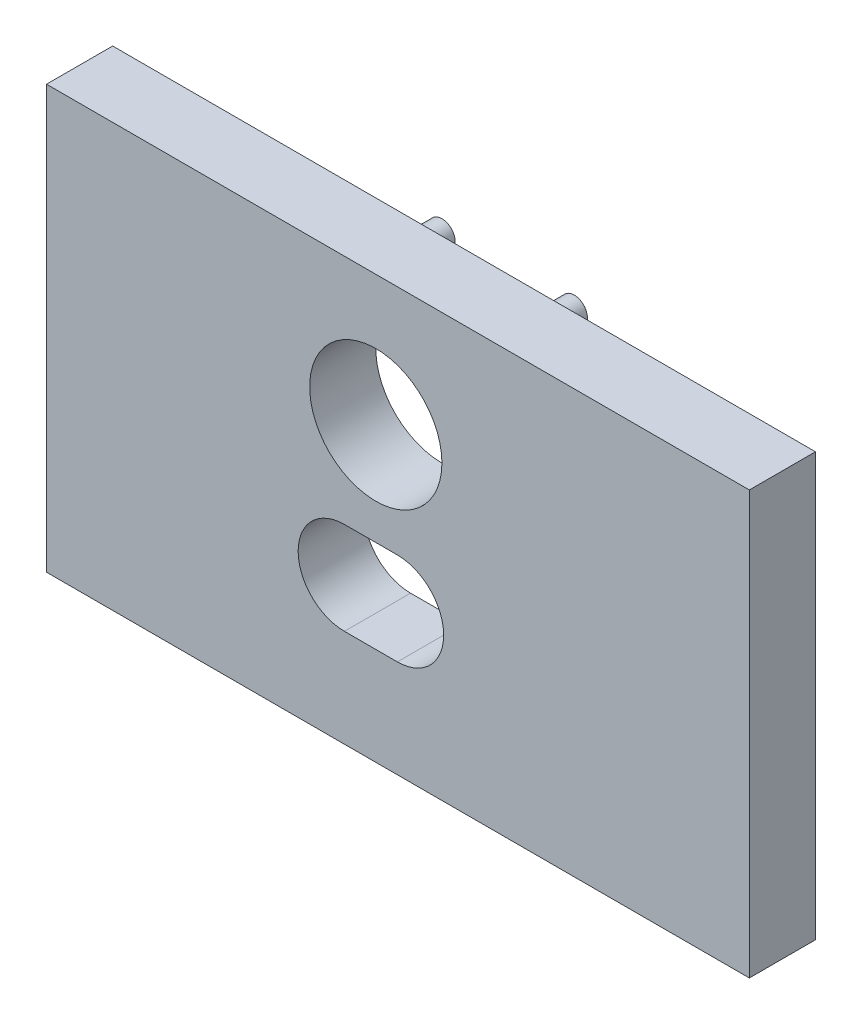
SolidWorks part; units mm, degrees
ref_plane "前视基准面" through (0, 0, 0) normal (0, 0, 1) x (1, 0, 0)
ref_plane "上视基准面" through (0, 0, 0) normal (0, 1, 0) x (1, 0, 0)
ref_plane "右视基准面" through (0, 0, 0) normal (1, 0, 0) x (0, 0, -1)
other "Configuration Table"
sketch "草图1" plane through (0, 0, 0) normal (0, 0, 1) x (1, 0, 0)
  line L1 (-40.8719, 31.4899) -> (12.2616, 31.4899)
  line L2 (-40.8719, 31.4899) -> (-40.8719, -0.4645)
  line L3 (-40.8719, -0.4645) -> (12.2616, -0.4645)
  line L4 (12.2616, 31.4899) -> (12.2616, -0.4645)
extrude "凸台-拉伸1" add sketch "草图1" along normal blind 5
sketch "草图2" plane through (0, 0, 0) normal (0, 0, -1) x (-1, 0, 0)
  line L0 (-12.2616, -0.4645) -> (-12.2616, 31.4899) construction
  line L1 (-10.2616, 29.4899) -> (38.8719, 29.4899)
  line L2 (-10.2616, 29.4899) -> (-10.2616, 1.5355)
  line L3 (-10.2616, 1.5355) -> (38.8719, 1.5355)
  line L4 (38.8719, 29.4899) -> (38.8719, 1.5355)
  line L5 (-12.2616, 31.4899) -> (40.8719, 31.4899) construction
  line L6 (40.8719, 31.4899) -> (40.8719, -0.4645) construction
  line L7 (40.8719, -0.4645) -> (-12.2616, -0.4645) construction
  line L9 (-12.2616, 31.4899) -> (40.8719, 31.4899)
  line L10 (-12.2616, 31.4899) -> (-12.2616, -0.4645)
  line L11 (-12.2616, -0.4645) -> (40.8719, -0.4645)
  line L12 (40.8719, 31.4899) -> (40.8719, -0.4645)
  dimension "D1" = 2
  dimension "D2" = 2
  dimension "D3" = 2
  dimension "D4" = 2
extrude "切除-拉伸1" [suppressed] cut sketch "草图2" against normal blind 3
sketch "草图3" plane through (0, 0, 0) normal (0, 0, -1) x (-1, 0, 0)
  line L1 (27.837, -21.8879) -> (-73.163, -21.8879)
  line L2 (27.837, -21.8879) -> (27.837, 29.1121)
  line L3 (27.837, 29.1121) -> (-73.163, 29.1121)
  line L4 (-73.163, -21.8879) -> (-73.163, 29.1121)
  line L5 (27.837, -21.8879) -> (-73.163, 29.1121) construction
  line L6 (27.837, 29.1121) -> (-73.163, -21.8879) construction
  point P0 (-22.663, 3.6121)
  point P5 (-22.663, 3.6121)
  dimension "D1" = 51
  dimension "D2" = 101
extrude "切除-拉伸2" [suppressed] cut sketch "草图3" against normal blind 4.5
sketch "草图4" [suppressed] plane through (0, 0, 0) normal (0, 0, -1) x (-1, 0, 0)
  line L0 (-93.163, -23.8879) -> (-85.163, -23.8879)
  line L1 (-93.163, 39.1121) -> (-85.163, 39.1121)
  line L2 (-93.163, 39.1121) -> (-93.163, 31.1121)
  line L3 (-93.163, 31.1121) -> (-85.163, 31.1121)
  line L4 (-85.163, 39.1121) -> (-85.163, 31.1121)
  line L5 (-93.163, -23.8879) -> (-93.163, -31.8879)
  line L6 (-93.163, -31.8879) -> (-85.163, -31.8879)
  line L7 (-85.163, -23.8879) -> (-85.163, -31.8879)
  line L8 (34.837, 39.1121) -> (42.837, 39.1121)
  line L9 (34.837, 39.1121) -> (34.837, 31.1121)
  line L10 (34.837, 31.1121) -> (42.837, 31.1121)
  line L11 (42.837, 39.1121) -> (42.837, 31.1121)
  line L12 (34.837, -23.8879) -> (42.837, -23.8879)
  line L13 (34.837, -23.8879) -> (34.837, -31.8879)
  line L14 (34.837, -31.8879) -> (42.837, -31.8879)
  line L15 (42.837, -23.8879) -> (42.837, -31.8879)
  dimension "D1" = 8
  dimension "D2" = 8
  dimension "D3" = 8
extrude "凸台-拉伸2" [suppressed] add sketch "草图4" along normal blind 8
sketch "草图5" [suppressed] plane through (0, 0, 4.5) normal (0, 0, -1) x (-1, 0, 0)
  circle A4 centre (-70.0525, 26.7137) radius 1.5
  circle A5 centre (-69.9255, -19.2603) radius 1.5
  circle A6 centre (24.8167, -19.0063) radius 1.5
  circle A7 centre (24.8167, 26.7137) radius 1.5
extrude "凸台-拉伸3" [suppressed] add sketch "草图5" along normal blind 1
sketch "草图6" [suppressed] plane through (0, 0, 3.5) normal (0, 0, -1) x (-1, 0, 0)
  circle A0 centre (-70.0525, 26.7137) radius 1
  circle A1 centre (-69.9255, -19.2603) radius 1
  circle A2 centre (24.8167, -19.0063) radius 1
  circle A3 centre (24.8167, 26.7137) radius 1
extrude "凸台-拉伸4" [suppressed] add sketch "草图6" along normal blind 3
hole_wizard "M3 六角凹锥坑螺钉的锥形沉头孔1" [suppressed] positions "3D草图1" profile "草图8" countersink size "M3" standard "ISO"
sketch3d "3D草图1"
  point P0 (-86.9377, 36.3345, -2.5)
  point P3 (-86.9377, -26.6655, -2.5)
sketch "草图8" plane through (-44.837, 35.1121, -4) normal (0, 1, 0) x (0, 0, 1)
  line L0 (0, 0) -> (0, 12)
  line L1 (0, 12) -> (1.7, 10.9785)
  line L2 (1.7, 10.9785) -> (1.7, 1.66)
  line L3 (1.7, 1.66) -> (3.36, 0)
  line L4 (3.36, 0) -> (0, 0)
  line L5 (-1.7, 1.66) -> (-3.36, 0) construction
  line L6 (0, 12) -> (-1.7, 10.9785) construction
  line L7 (0, -6.35) -> (0, 107.95) construction
  dimension "孔直径" = 3.4
  dimension "孔深度" = 12
  dimension "近端锥形沉头孔直径" = 6.72
  dimension "近端锥形沉头孔角度" = 90
  dimension "导头角度" = 118
hole_wizard "M3 六角凹锥坑螺钉的锥形沉头孔2" [suppressed] positions "3D草图2" profile "草图9" countersink size "M3" standard "ISO"
sketch3d "3D草图2"
  point P0 (53.0623, -26.6655, -2.5)
  point P3 (53.0623, 36.3345, -2.5)
sketch "草图9" plane through (95.163, -27.8879, -4) normal (0, 1, 0) x (0, 0, -1)
  line L0 (0, 0) -> (0, 12)
  line L1 (0, 12) -> (1.7, 10.9785)
  line L2 (1.7, 10.9785) -> (1.7, 1.66)
  line L3 (1.7, 1.66) -> (3.36, 0)
  line L4 (3.36, 0) -> (0, 0)
  line L5 (-1.7, 1.66) -> (-3.36, 0) construction
  line L6 (0, 12) -> (-1.7, 10.9785) construction
  line L7 (0, -6.35) -> (0, 107.95) construction
  dimension "孔直径" = 3.4
  dimension "孔深度" = 12
  dimension "近端锥形沉头孔直径" = 6.72
  dimension "近端锥形沉头孔角度" = 90
  dimension "导头角度" = 118
thread "螺纹线1" [suppressed] pitch 0.5 start angle 0, offset 0, length 8, pitch 0.5, diameter 3.4
ref_plane "基准面1" through (85.163, 35.1121, -5.7) normal (0, -1, 0) x (0, 0, -1)
sketch "螺纹线轮廓1" plane through (85.163, 35.1121, -5.7) normal (0, -1, 0) x (0, 0, -1)
  line L0 (0, 0) -> (0, 0.5) construction
  line L11 (0, 0) -> (0, 0.4375)
  line L12 (0, 0.4375) -> (-0.2706, 0.2812)
  line L13 (-0.2706, 0.2812) -> (-0.2706, 0.1562)
  line L15 (-0.2706, 0.1562) -> (0, 0)
  line L17 (-0.2706, 0.2187) -> (0, 0.2187) construction
  point P2 (0, 0)
  dimension "Pitch" = 0.5
  dimension "Profile_Angle" = 60
  dimension "Profile_Land" = 0.125
  dimension "Profile_Height" = 0.2706
sketch "草图10" [suppressed] plane through (0, -33.8879, 0) normal (0, -1, 0) x (1, 0, 0)
  line L1 (-44.837, 5) -> (95.163, 5)
  line L2 (-44.837, 5) -> (-44.837, 3)
  line L3 (-44.837, 3) -> (95.163, 3)
  line L4 (95.163, 5) -> (95.163, 3)
extrude "凸台-拉伸5" [suppressed] add sketch "草图10" along normal blind 5
sketch "草图11" [suppressed] plane through (0, 0, 0) normal (0, 0, -1) x (-1, 0, 0)
  line L0 (27.837, 29.1121) -> (-73.163, 29.1121) construction
  line L1 (12.837, 29.1121) -> (27.837, 29.1121)
  line L2 (12.837, 29.1121) -> (12.837, 28.1121)
  line L3 (12.837, -21.8879) -> (27.837, -21.8879)
  line L4 (27.837, 29.1121) -> (27.837, -21.8879)
  line L5 (12.837, -20.8879) -> (12.837, -21.8879)
  line L6 (12.837, 28.1121) -> (26.837, 28.1121)
  line L8 (12.837, -20.8879) -> (26.837, -20.8879)
  line L9 (26.837, 28.1121) -> (26.837, -20.8879)
  dimension "D1" = 1
  dimension "D2" = 1
  dimension "D3" = 1
  dimension "D4" = 15
extrude "凸台-拉伸6" [suppressed] add sketch "草图11" against normal blind 1
thread "螺纹线2" [suppressed] pitch 0.5 start angle 0, offset 0, length 8, pitch 0.5, diameter 3.4
ref_plane "基准面2" through (-34.837, 35.1121, -2.3) normal (0, -1, 0) x (0, 0, 1)
sketch "螺纹线轮廓2" plane through (-34.837, 35.1121, -2.3) normal (0, -1, 0) x (0, 0, 1)
  line L0 (0, 0) -> (0, 0.5) construction
  line L11 (0, 0) -> (0, 0.4375)
  line L12 (0, 0.4375) -> (-0.2706, 0.2812)
  line L13 (-0.2706, 0.2812) -> (-0.2706, 0.1562)
  line L15 (-0.2706, 0.1562) -> (0, 0)
  line L17 (-0.2706, 0.2187) -> (0, 0.2187) construction
  point P2 (0, 0)
  dimension "Pitch" = 0.5
  dimension "Profile_Angle" = 60
  dimension "Profile_Land" = 0.125
  dimension "Profile_Height" = 0.2706
thread "螺纹线3" [suppressed] pitch 0.5 start angle 0, offset 0, length 8, pitch 0.5, diameter 3.4
ref_plane "基准面3" through (85.163, -27.8879, -5.7) normal (0, -1, 0) x (0, 0, -1)
sketch "螺纹线轮廓3" plane through (85.163, -27.8879, -5.7) normal (0, -1, 0) x (0, 0, -1)
  line L0 (0, 0) -> (0, 0.5) construction
  line L11 (0, 0) -> (0, 0.4375)
  line L12 (0, 0.4375) -> (-0.2706, 0.2812)
  line L13 (-0.2706, 0.2812) -> (-0.2706, 0.1562)
  line L15 (-0.2706, 0.1562) -> (0, 0)
  line L17 (-0.2706, 0.2187) -> (0, 0.2187) construction
  point P2 (0, 0)
  dimension "Pitch" = 0.5
  dimension "Profile_Angle" = 60
  dimension "Profile_Land" = 0.125
  dimension "Profile_Height" = 0.2706
thread "螺纹线4" [suppressed] pitch 0.5 start angle 0, offset 0, length 8, pitch 0.5, diameter 3.4
ref_plane "基准面4" through (-34.837, -27.8879, -2.3) normal (0, -1, 0) x (0, 0, 1)
sketch "螺纹线轮廓4" plane through (-34.837, -27.8879, -2.3) normal (0, -1, 0) x (0, 0, 1)
  line L0 (0, 0) -> (0, 0.5) construction
  line L11 (0, 0) -> (0, 0.4375)
  line L12 (0, 0.4375) -> (-0.2706, 0.2812)
  line L13 (-0.2706, 0.2812) -> (-0.2706, 0.1562)
  line L15 (-0.2706, 0.1562) -> (0, 0)
  line L17 (-0.2706, 0.2187) -> (0, 0.2187) construction
  point P2 (0, 0)
  dimension "Pitch" = 0.5
  dimension "Profile_Angle" = 60
  dimension "Profile_Land" = 0.125
  dimension "Profile_Height" = 0.2706
sketch "草图12" [suppressed] plane through (0, 0, 4.5) normal (0, 0, -1) x (-1, 0, 0)
  line L0 (-61.8607, -1.1766) -> (-61.8607, -10.1766)
  line L5 (-61.8607, -10.1766) -> (-47.8607, -10.1766)
  line L6 (-47.8607, -1.1766) -> (-47.8607, -10.1766)
  line L7 (-61.8607, -1.1766) -> (-47.8607, -1.1766)
extrude "凸台-拉伸7" [suppressed] add sketch "草图12" along normal blind 5
sketch "草图13" plane through (0, 0, 5) normal (0, 0, 1) x (1, 0, 0)
  circle A0 centre (-15.9792, 21.6315) radius 5
  dimension "D1" = 10
extrude "切除-拉伸3" cut sketch "草图13" against normal blind 10
sketch "草图14" plane through (0, 0, 0) normal (0, 0, -1) x (-1, 0, 0)
  line L0 (15.9792, 21.6315) -> (15.9792, 27.4907) construction
  line L1 (10.9792, 21.6315) -> (10.9792, 26.6315) construction
  line L2 (20.9792, 21.6315) -> (20.9792, 26.6315) construction
  line L3 (15.9792, 25.5402) -> (10.9792, 25.5402) construction
  line L4 (10.9792, 25.5402) -> (20.9792, 25.5402) construction
  line L5 (15.9792, 26.6315) -> (10.9792, 26.6315) construction
  line L6 (15.9792, 26.6315) -> (20.9792, 26.6315) construction
  circle A0 centre (15.9792, 21.6315) radius 5 construction
  circle A1 centre (10.9792, 26.6315) radius 1
  circle A2 centre (20.9792, 26.6315) radius 1
  dimension "D1" = 2
  dimension "D2" = 2
extrude "凸台-拉伸8" add sketch "草图14" along normal blind 5
sketch "草图15" plane through (0, 0, 5) normal (0, 0, 1) x (1, 0, 0)
  line L2 (-18.3493, 10.4275) -> (-14.3493, 10.4275) construction
  line L3 (-18.3493, 13.9275) -> (-14.3493, 13.9275)
  line L4 (-18.3493, 6.9275) -> (-14.3493, 6.9275)
  arc A0 (-18.3493, 13.9275) -> (-18.3493, 6.9275) centre (-18.3493, 10.4275) ccw
  arc A1 (-14.3493, 6.9275) -> (-14.3493, 13.9275) centre (-14.3493, 10.4275) ccw
  point P0 (-10.8493, 10.4275)
  point P1 (-21.8493, 10.4275)
  point P6 (-16.3493, 10.4275)
  dimension "D1" = 7
  dimension "D2" = 11
extrude "切除-拉伸4" cut sketch "草图15" against normal blind 5
